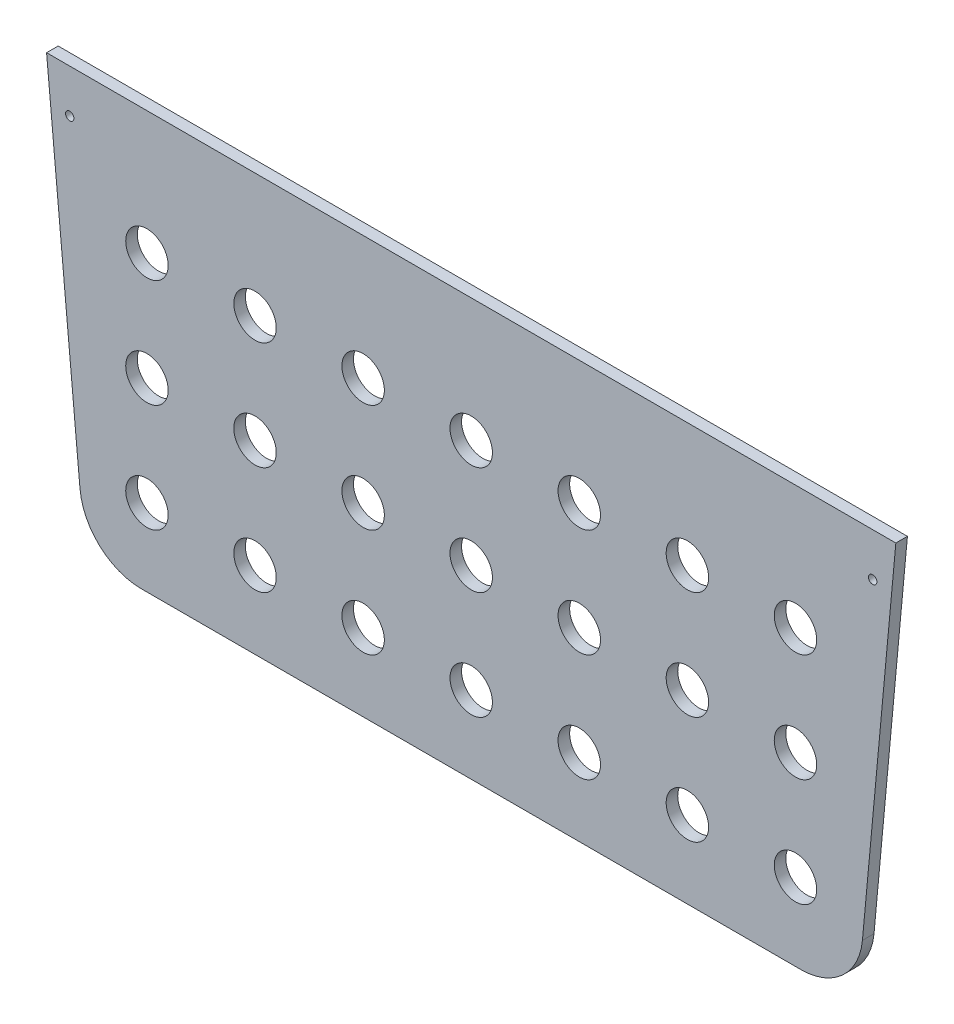
SolidWorks part; units mm, degrees
ref_plane "Front Plane" through (0, 0, 0) normal (0, 0, 1) x (1, 0, 0)
ref_plane "Top Plane" through (0, 0, 0) normal (0, 1, 0) x (1, 0, 0)
ref_plane "Right Plane" through (0, 0, 0) normal (1, 0, 0) x (0, 0, -1)
sketch "Sketch1" plane through (0, 0, 0) normal (0, 0, 1) x (1, 0, 0)
  line L0 (-174.625, 0) -> (174.625, 0)
  line L1 (-135.5932, -171.45) -> (135.5932, -171.45)
  line L2 (-174.625, 0) -> (-160.885, -148.3918)
  line L3 (160.885, -148.3918) -> (174.625, 0)
  line L4 (0, 0) -> (0, -171.45) construction
  arc A0 (135.5932, -171.45) -> (160.885, -148.3918) centre (135.5932, -146.05) ccw
  arc A1 (-135.5932, -171.45) -> (-160.885, -148.3918) centre (-135.5932, -146.05) cw
  circle A2 centre (-44.45, -139.7) radius 8.7312
  circle A3 centre (-88.9, -139.7) radius 8.7312
  circle A4 centre (-133.35, -139.7) radius 8.7312
  circle A5 centre (-88.9, -95.25) radius 8.7313
  circle A6 centre (-133.35, -95.25) radius 8.7313
  circle A7 centre (-88.9, -50.8) radius 8.7313
  circle A8 centre (-133.35, -50.8) radius 8.7313
  circle A9 centre (-44.45, -95.25) radius 8.7312
  circle A10 centre (-44.45, -50.8) radius 8.7313
  circle A11 centre (0, -139.7) radius 8.7312
  circle A12 centre (44.45, -139.7) radius 8.7312
  circle A13 centre (88.9, -139.7) radius 8.7312
  circle A14 centre (133.35, -139.7) radius 8.7312
  circle A15 centre (44.45, -95.25) radius 8.7313
  circle A16 centre (88.9, -95.25) radius 8.7313
  circle A17 centre (133.35, -95.25) radius 8.7313
  circle A18 centre (44.45, -50.8) radius 8.7312
  circle A19 centre (88.9, -50.8) radius 8.7313
  circle A20 centre (133.35, -50.8) radius 8.7313
  circle A21 centre (0, -95.25) radius 8.7313
  circle A22 centre (0, -50.8) radius 8.7312
  point P4 (0, 0)
  point P7 (0, -171.45)
  point P11 (158.75, -171.45)
  point P14 (-158.75, -171.45)
  dimension "D4" = 25.4
  dimension "D5" = 31.75
  dimension "D6" = 114.3
  dimension "D7" = 17.4625
  dimension "D8" = 3
  dimension "D1" = 171.45
  dimension "D2" = 349.25
  dimension "D3" = 317.5
  dimension "D9" = 3
  dimension "D10" = 2
  dimension "D11" = 4
  dimension "D12" = 3
extrude "Boss-Extrude1" add sketch "Sketch1" along normal blind 4.7625
hole_wizard "Tap Drill for #8-32 Tap1" positions "Sketch3" profile "Sketch4" hole size "#8-32" standard "ANSI Inch" end condition through all
sketch "Sketch3" plane through (0, 0, 4.7625) normal (0, 0, 1) x (1, 0, 0)
  point P0 (165.1, -17.78)
  point P3 (-165.1, -17.78)
sketch "Sketch4" plane through (165.1, -17.78, 4.7625) normal (1, 0, 0) x (0, -1, 0)
  line L0 (0, 0) -> (0, 4.7625)
  line L1 (0, 4.7625) -> (1.7272, 4.7625)
  line L2 (1.7272, 4.7625) -> (1.7272, 0)
  line L5 (1.7272, 0) -> (0, 0)
  line L11 (0, -6.35) -> (0, 107.95) construction
  dimension "Thru Hole Dia." = 3.4544
  dimension "Thru Hole Depth" = 4.7625
